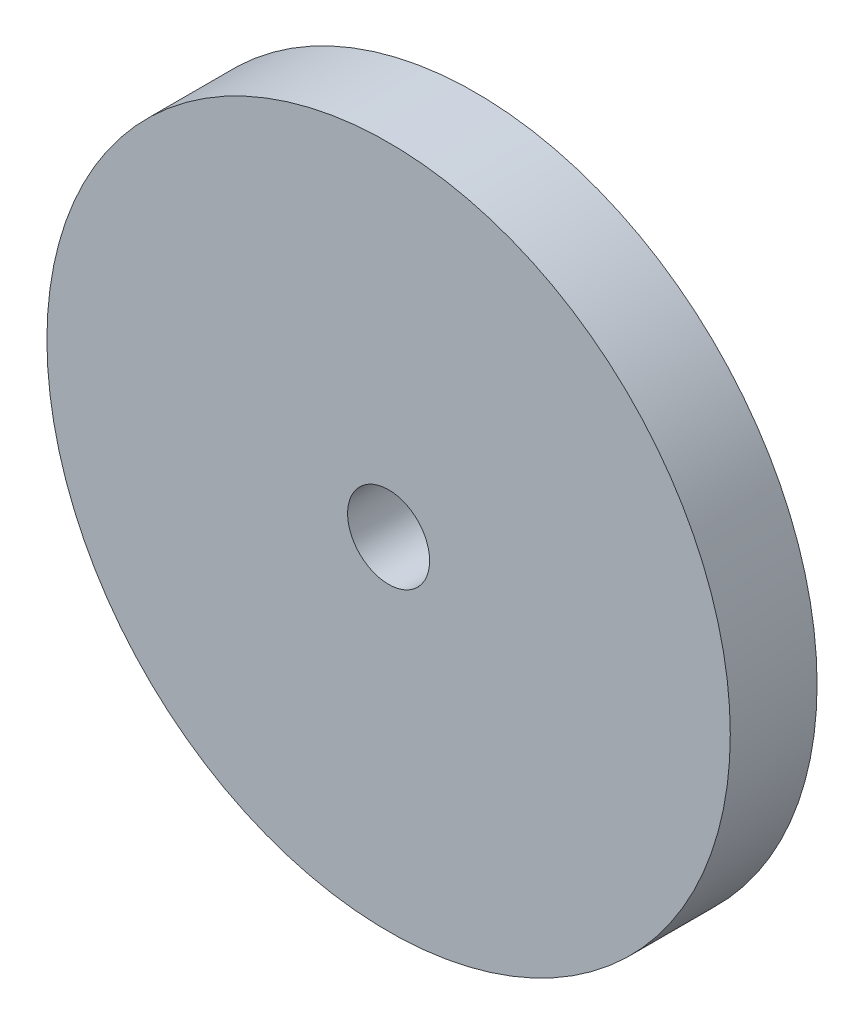
SolidWorks part; units mm, degrees
ref_plane "Front Plane" through (0, 0, 0) normal (0, 0, 1) x (1, 0, 0)
ref_plane "Top Plane" through (0, 0, 0) normal (0, 1, 0) x (1, 0, 0)
ref_plane "Right Plane" through (0, 0, 0) normal (1, 0, 0) x (0, 0, -1)
sketch "Sketch1" plane through (0, 0, 0) normal (0, 0, 1) x (1, 0, 0)
  circle A0 centre (0, 0) radius 25
  circle A1 centre (0, 0) radius 3
  dimension "D1" = 50
  dimension "D2" = 6
extrude "Boss-Extrude1" add sketch "Sketch1" along normal blind 6.35
